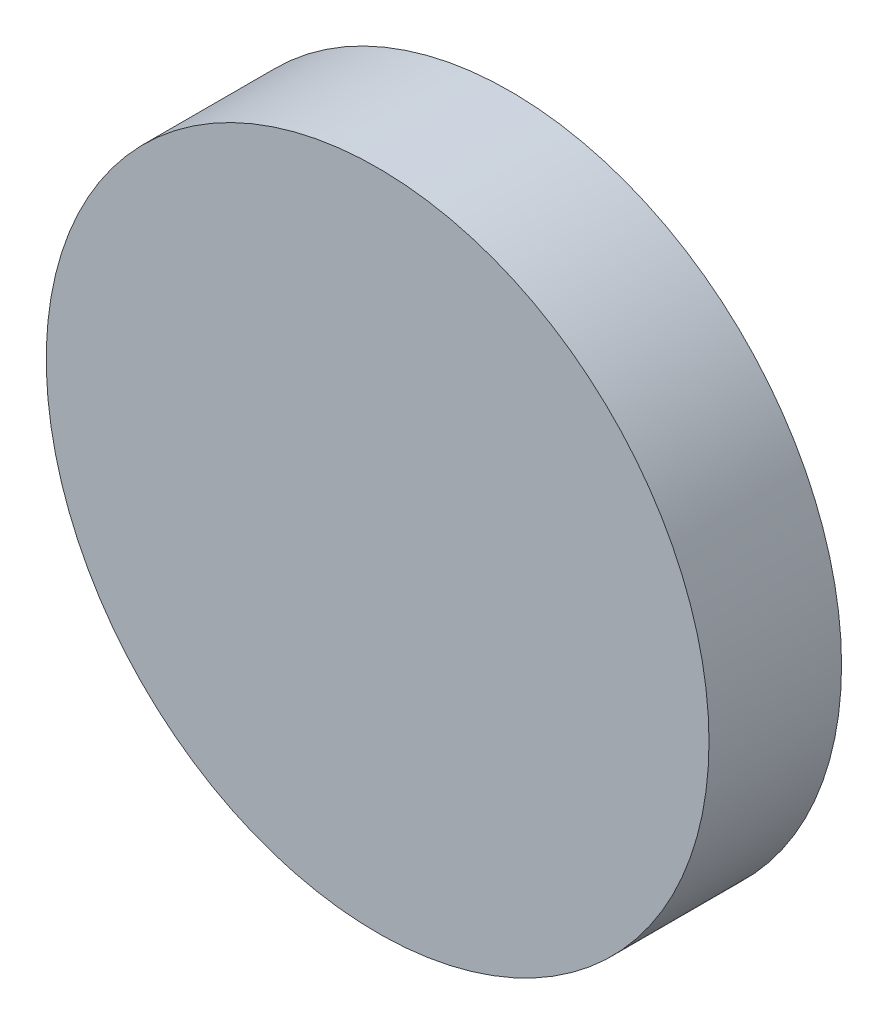
SolidWorks part; units mm, degrees
ref_plane "Front Plane" through (0, 0, 0) normal (0, 0, 1) x (1, 0, 0)
ref_plane "Top Plane" through (0, 0, 0) normal (0, 1, 0) x (1, 0, 0)
ref_plane "Right Plane" through (0, 0, 0) normal (1, 0, 0) x (0, 0, -1)
sketch "Sketch1" plane through (0, 0, 0) normal (0, 0, 1) x (1, 0, 0)
  circle A0 centre (0, 0) radius 12.7
  dimension "D1" = 25.4
extrude "Boss-Extrude1" add sketch "Sketch1" along normal blind 5.08
